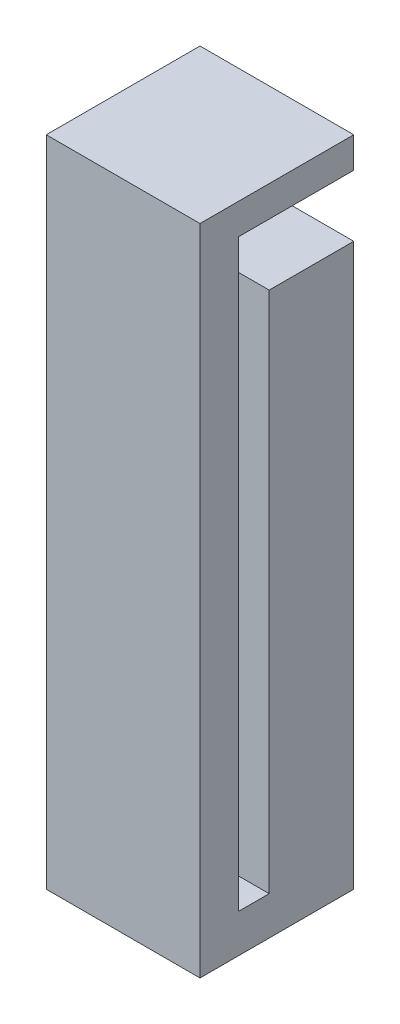
SolidWorks part; units mm, degrees
ref_plane "Front Plane" through (0, 0, 0) normal (0, 0, 1) x (1, 0, 0)
ref_plane "Top Plane" through (0, 0, 0) normal (0, 1, 0) x (1, 0, 0)
ref_plane "Right Plane" through (0, 0, 0) normal (1, 0, 0) x (0, 0, -1)
sketch "Sketch1" plane through (0, 0, 0) normal (0, 1, 0) x (1, 0, 0)
  line L1 (0, 0) -> (10, 0)
  line L2 (0, 0) -> (0, 10)
  line L3 (0, 10) -> (10, 10)
  line L4 (10, 0) -> (10, 10)
  dimension "D1" = 10
extrude "Boss-Extrude1" add sketch "Sketch1" along normal blind 40
sketch "Sketch3" plane through (0, 0, -10) normal (0, 0, -1) x (-1, 0, 0)
  line L0 (-10, 40) -> (-10, 0) construction
  line L1 (-2.5, 38) -> (-10, 38)
  line L2 (-2.5, 38) -> (-2.5, 34)
  line L3 (-2.5, 34) -> (-10, 34)
  line L4 (-10, 38) -> (-10, 34)
  line L5 (-10, 40) -> (0, 40) construction
  line L6 (0, 40) -> (0, 0) construction
  dimension "D1" = 2
  dimension "D2" = 4
  dimension "D3" = 2.5
extrude "Cut-Extrude1" cut sketch "Sketch3" against normal offset from surface (7.5 mm away) 2.5 up to face at (5, 20, 0)
sketch "Sketch4" plane through (0, 0, 0) normal (0, -1, 0) x (1, 0, 0)
  line L0 (2.5, -2.5) -> (2.5, -10) construction
  line L1 (2.5, -2.5) -> (2.5, -10)
  line L2 (2.5, -2.5) -> (10, -2.5) construction
  line L3 (2.5, -2.5) -> (10, -2.5)
  line L4 (10, -10) -> (0, -10) construction
  line L5 (10, -2.5) -> (2.5, -2.5)
  line L6 (10, -2.5) -> (10, -4.5)
  line L7 (10, -4.5) -> (2.5, -4.5)
  line L8 (2.5, -2.5) -> (2.5, -4.5)
  line L9 (4.5, -10) -> (2.5, -10)
  line L10 (4.5, -10) -> (4.5, -4.5)
  line L11 (4.5, -4.5) -> (2.5, -4.5)
  line L12 (2.5, -10) -> (2.5, -4.5)
  line M10 (0, -10) -> (10, -10)
  line M11 (10, -10) -> (10, 0)
  dimension "D1" = 2
  dimension "D2" = 2
extrude "Cut-Extrude2" cut sketch "Sketch4" against normal up to surface (38 mm away) contours L7 L3 L1 M11 | L10 L7 L1 M10 up to face at (6.25, 38, -6.25)
sketch "Sketch5" plane through (0, 0, 0) normal (0, -1, 0) x (1, 0, 0)
  line L1 (0, 0) -> (10, 0)
  line L2 (0, 0) -> (0, -10)
  line L3 (0, -10) -> (10, -10)
  line L4 (10, 0) -> (10, -10)
extrude "Boss-Extrude2" add sketch "Sketch5" along normal blind 2.5
sketch "Sketch6" plane through (0, 0, 0) normal (0, 1, 0) x (1, 0, 0)
  line L0 (10, 4.5) -> (4.5, 4.5) construction
  line L1 (2.5, 2.5) -> (6.5, 2.5)
  line L2 (2.5, 2.5) -> (2.5, 4.5)
  line L3 (2.5, 4.5) -> (6.5, 4.5)
  line L4 (6.5, 2.5) -> (6.5, 4.5)
  line L5 (4.5, 10) -> (4.5, 4.5) construction
  line L6 (2.5, 4.5) -> (4.5, 4.5)
  line L7 (2.5, 4.5) -> (2.5, 6.5)
  line L8 (2.5, 6.5) -> (4.5, 6.5)
  line L9 (4.5, 4.5) -> (4.5, 6.5)
  line L10 (3.5, 2.5) -> (3.5, 6.5) construction
  point P14 (3.5, 6.4879)
  line M7 (10, 4.5) -> (4.5, 4.5)
  line M8 (4.5, 4.5) -> (4.5, 10)
  line M10 (2.5, 10) -> (2.5, 2.5)
  line M11 (2.5, 2.5) -> (10, 2.5)
  dimension "D1" = 4
extrude "Boss-Extrude3" add sketch "Sketch6" along normal up to surface (38 mm away) contours L10 L1 L4 L6 M7 | L10 L6 L8 M8 | L3 L10 L8 M10 | L10 L3 M11 M10 up to face at (6.25, 38, -6.25)
